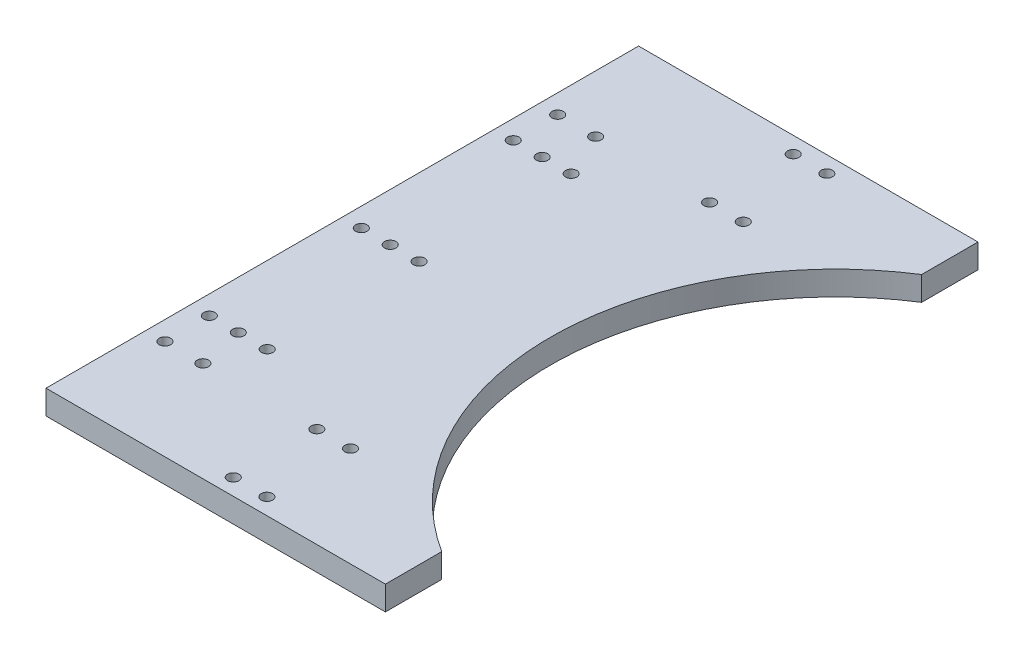
SolidWorks part; units mm, degrees
ref_plane "Front Plane" through (0, 0, 0) normal (0, 0, 1) x (1, 0, 0)
ref_plane "Top Plane" through (0, 0, 0) normal (0, 1, 0) x (1, 0, 0)
ref_plane "Right Plane" through (0, 0, 0) normal (1, 0, 0) x (0, 0, -1)
sketch "Sketch1" plane through (0, 0, 0) normal (0, 1, 0) x (1, 0, 0)
  line L0 (0, 0) -> (49.85, 0)
  line L1 (0, 0) -> (0, 31.3)
  line L4 (49.85, 0) -> (57.85, 0)
  line L6 (0, 78) -> (77.3048, 78) construction
  line L8 (49.85, 156) -> (57.85, 156)
  line L11 (0, 156) -> (0, 124.7)
  line L12 (0, 156) -> (49.85, 156)
  line L13 (89.35, 156) -> (89.35, 141.17) construction
  line L14 (57.85, 0) -> (89.35, 0)
  line L15 (57.85, 156) -> (89.35, 156)
  line L16 (89.35, 156) -> (89.35, 141.17)
  line L17 (0, 124.7) -> (0, 31.3)
  line L18 (89.35, 14.83) -> (89.35, 0) construction
  line L19 (89.35, 14.83) -> (89.35, 0)
  circle A0 centre (45, 26.3) radius 1.5
  circle A1 centre (45, 4.3) radius 1.5
  circle A2 centre (15, 26.3) radius 1.5
  circle A3 centre (5, 26.3) radius 1.5
  circle A4 centre (53.85, 26.3) radius 1.5
  circle A5 centre (53.85, 4.3) radius 1.5
  circle A6 centre (53.85, 151.7) radius 1.5
  circle A7 centre (53.85, 129.7) radius 1.5
  circle A8 centre (5, 129.7) radius 1.5
  circle A9 centre (15, 129.7) radius 1.5
  circle A10 centre (45, 151.7) radius 1.5
  circle A11 centre (45, 129.7) radius 1.5
  arc A12 (89.35, 141.17) -> (89.35, 14.83) centre (129.7796, 78) ccw
  circle A13 centre (5, 118) radius 1.5
  circle A14 centre (5, 78) radius 1.5
  circle A15 centre (5, 38) radius 1.5
  circle A16 centre (12.62, 38) radius 1.5
  circle A17 centre (12.62, 78) radius 1.5
  circle A18 centre (12.62, 118) radius 1.5
  circle A19 centre (20.24, 38) radius 1.5
  circle A20 centre (20.24, 78) radius 1.5
  circle A21 centre (20.24, 118) radius 1.5
  point P41 (89.35, 141.17)
  point P43 (89.35, 14.83)
  dimension "D5" = 3
  dimension "D7" = 3
  dimension "D11" = 3
  dimension "D19" = 150
  dimension "D6" = 3
  dimension "D10" = 3
  dimension "D1" = 31.3
  dimension "D2" = 49.85
  dimension "D3" = 22
  dimension "D4" = 30
  dimension "D8" = 40
  dimension "D9" = 5
  dimension "D12" = 5
  dimension "D13" = 3
  dimension "D15" = 10
  dimension "D16" = 78
  dimension "D17" = 44.35
  dimension "D18" = 14.83
extrude "Boss-Extrude1" add sketch "Sketch1" along normal blind 6.35
